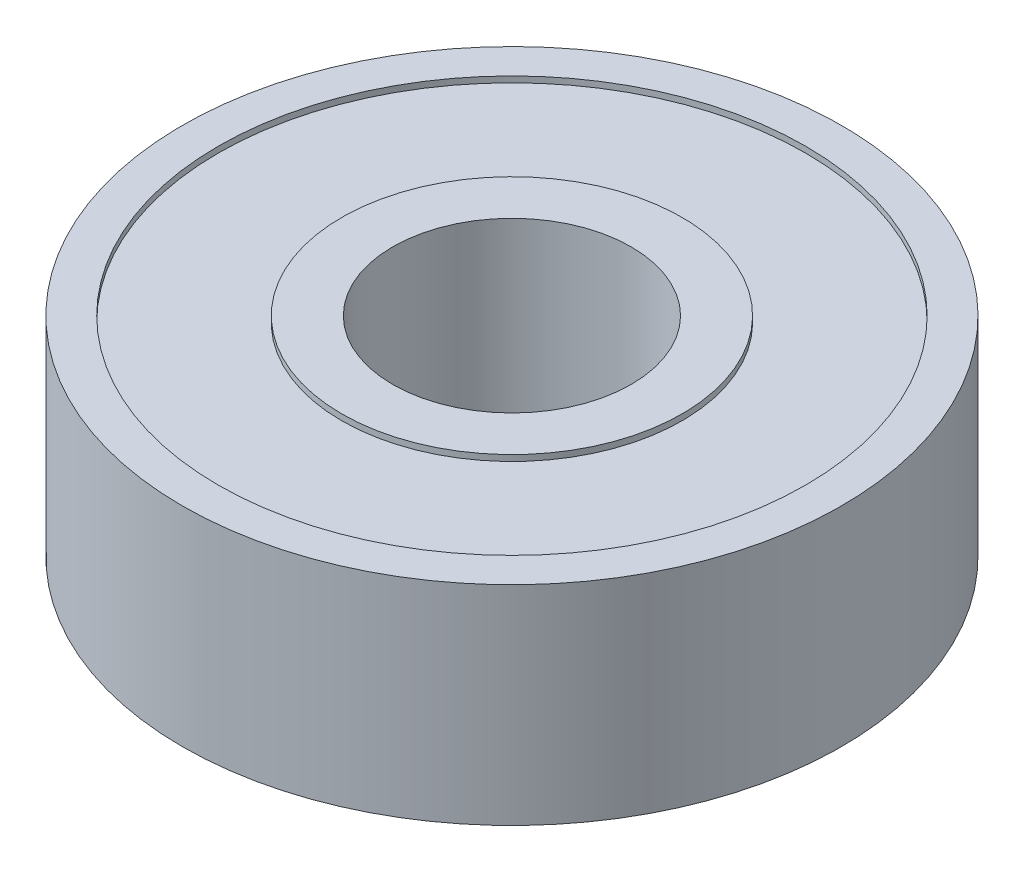
SolidWorks part; units mm, degrees
ref_plane "Front Plane" through (0, 0, 0) normal (0, 0, 1) x (1, 0, 0)
ref_plane "Top Plane" through (0, 0, 0) normal (0, 1, 0) x (1, 0, 0)
ref_plane "Right Plane" through (0, 0, 0) normal (1, 0, 0) x (0, 0, -1)
sketch "Sketch3" plane through (0, 0, 0) normal (0, 1, 0) x (1, 0, 0)
  circle A0 centre (0, 0) radius 3.98
  circle A1 centre (0, 0) radius 11
  dimension "D1" = 7.96
  dimension "D2" = 22
extrude "Boss-Extrude1" add sketch "Sketch3" along normal mid plane 6.96
sketch "Sketch4" plane through (0, 3.48, 0) normal (0, 1, 0) x (1, 0, 0)
  circle A0 centre (0, 0) radius 5.68
  circle A1 centre (0, 0) radius 3.98 construction
  circle A2 centre (0, 0) radius 9.8
  circle A3 centre (0, 0) radius 11 construction
  dimension "D1" = 1.7
  dimension "D2" = 1.2
extrude "Cut-Extrude1" cut sketch "Sketch4" against normal blind 0.2
mirror "Mirror1" about plane through (0, 0, 0) normal (0, 1, 0) of "Cut-Extrude1"
